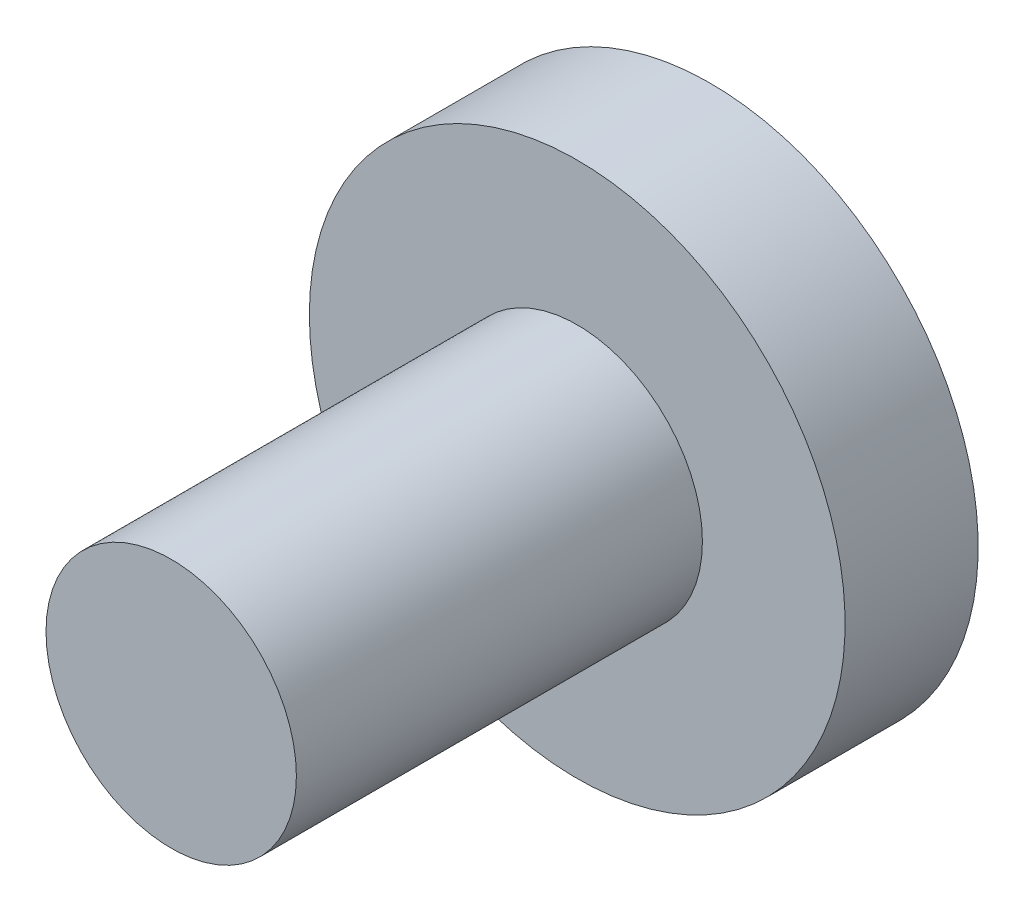
SolidWorks part; units mm, degrees
ref_plane "Front Plane" through (0, 0, 0) normal (0, 0, 1) x (1, 0, 0)
ref_plane "Top Plane" through (0, 0, 0) normal (0, 1, 0) x (1, 0, 0)
ref_plane "Right Plane" through (0, 0, 0) normal (1, 0, 0) x (0, 0, -1)
sketch "Sketch1" plane through (0, 0, 0) normal (0, 0, 1) x (1, 0, 0)
  circle A0 centre (-3.5693, 4.7947) radius 6.0325
  dimension "D1" = 12.065
extrude "Boss-Extrude1" add sketch "Sketch1" along normal blind 2.9972
sketch "Sketch2" plane through (0, 0, 2.9972) normal (0, 0, 1) x (1, 0, 0)
  circle A0 centre (-3.5693, 4.7947) radius 2.8194
  dimension "D1" = 5.6388
extrude "Boss-Extrude2" add sketch "Sketch2" along normal blind 9.144
